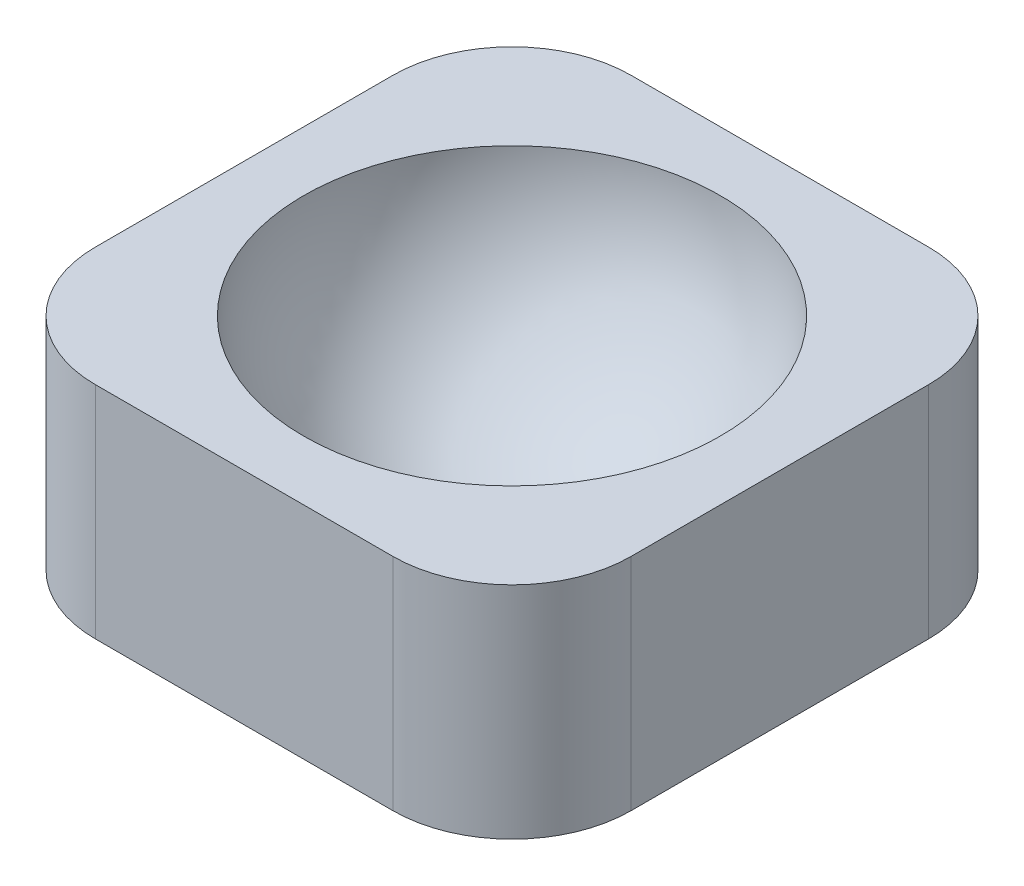
SolidWorks part; units mm, degrees
material "AISI 4340 Steel, normalized"
ref_plane "Front Plane" through (0, 0, 0) normal (0, 0, 1) x (1, 0, 0)
ref_plane "Top Plane" through (0, 0, 0) normal (0, 1, 0) x (1, 0, 0)
ref_plane "Right Plane" through (0, 0, 0) normal (1, 0, 0) x (0, 0, -1)
sketch "Sketch1" plane through (0, 0, 0) normal (0, 1, 0) x (1, 0, 0)
  line L1 (0, 0) -> (-114.3, 0)
  line L2 (0, 0) -> (0, 114.3)
  line L3 (0, 114.3) -> (-114.3, 114.3)
  line L4 (-114.3, 0) -> (-114.3, 114.3)
  circle A0 centre (-57.15, 57.15) radius 44.45
  point P7 (-101.6, 57.15)
  point P8 (-114.3, 57.15)
  point P9 (0, 57.15)
  point P10 (-57.15, 114.3)
  point P11 (-57.15, 0)
  point P13 (-57.15, 101.6)
  dimension "D1" = 88.9
  dimension "D2" = 12.7
  dimension "D3" = 12.7
extrude "Boss-Extrude1" add sketch "Sketch1" along normal blind 46.99 contours L4 L1 L2 L3 A0 | A0
sketch "Sketch2" plane through (0, 46.99, 0) normal (0, 1, 0) x (1, 0, 0)
  line L0 (-57.15, 114.3) -> (-57.15, 0) construction
  line L1 (0, 114.3) -> (-114.3, 114.3) construction
  line L2 (0, 0) -> (-114.3, 0) construction
  line L3 (-57.15, 101.6) -> (-57.15, 12.7)
  circle A0 centre (-57.15, 57.15) radius 44.45
  dimension "D1" = 88.9
revolve "Cut-Revolve1" cut sketch "Sketch2" angle 180 about L0
fillet "Fillet1" radius 25.4 4 edges at (0, 23.495, 0) (-114.3, 23.495, 0) (-114.3, 23.495, -114.3) (0, 23.495, -114.3)
sketch "Sketch3" plane through (0, 0, 0) normal (0, -1, 0) x (1, 0, 0)
  line L0 (-57.15, -114.3) -> (-57.15, 0) construction
  line L1 (-25.4, -114.3) -> (-88.9, -114.3) construction
  line L2 (-25.4, 0) -> (-88.9, 0) construction
  line L3 (0, -57.15) -> (-114.3, -57.15) construction
  line L4 (0, -25.4) -> (0, -88.9) construction
  line L5 (-114.3, -25.4) -> (-114.3, -88.9) construction
equation "\"D3@Sketch1\"=\"D2@Sketch1\""
